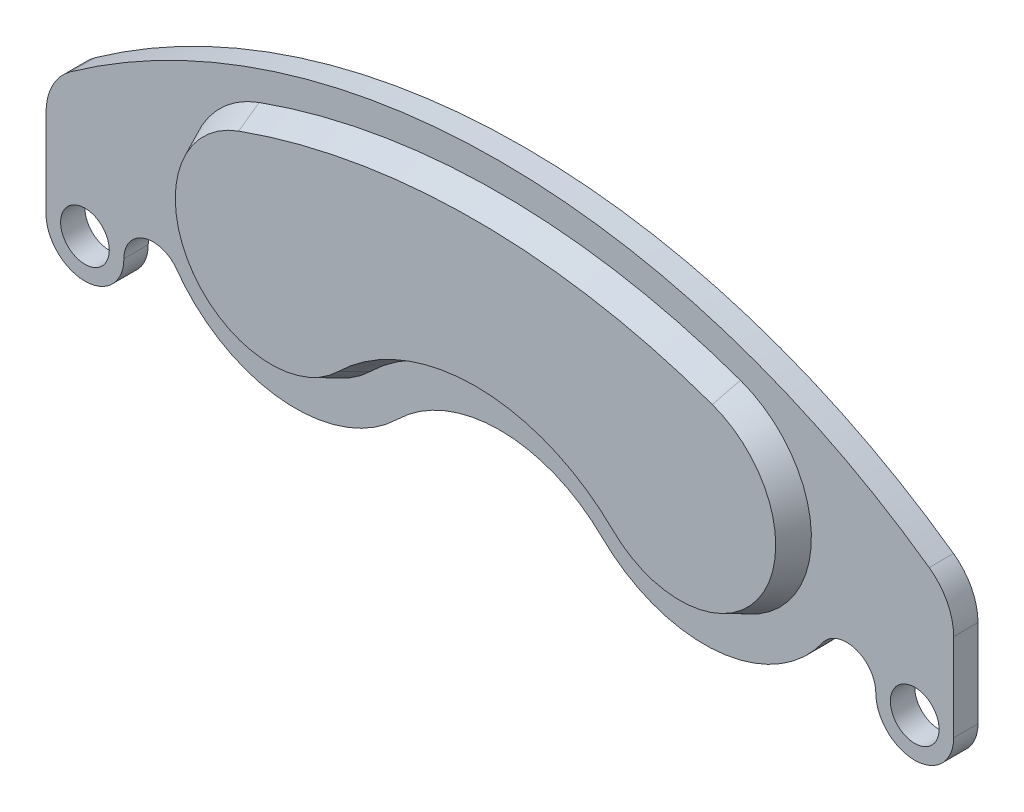
SolidWorks part; units mm, degrees
ref_plane "Front Plane" through (0, 0, 0) normal (0, 0, 1) x (1, 0, 0)
ref_plane "Top Plane" through (0, 0, 0) normal (0, 1, 0) x (1, 0, 0)
ref_plane "Right Plane" through (0, 0, 0) normal (1, 0, 0) x (0, 0, -1)
sketch "Sketch1" plane through (0, 0, 0) normal (0, 0, 1) x (1, 0, 0)
  line L0 (0, 0) -> (0, 108.8478) construction
  line L1 (-46.618, 57.0103) -> (-46.618, 48.0103)
  line L2 (46.618, 57.0103) -> (46.618, 48.0103)
  arc A0 (44.0995, 61.8969) -> (-44.0995, 61.8969) centre (0, 0) ccw
  arc A1 (-44.0995, 61.8969) -> (-46.618, 57.0103) centre (-40.618, 57.0103) ccw
  arc A2 (-46.618, 48.0103) -> (-38.618, 48.0103) centre (-42.618, 48.0103) ccw
  arc A3 (-38.618, 48.0103) -> (-33.3012, 49.9163) centre (-35.618, 48.0103) cw
  arc A4 (-33.3012, 49.9163) -> (-10.5, 47.7879) centre (-21, 58.5) ccw
  arc A5 (-10.5, 47.7879) -> (10.5, 47.7879) centre (0, 37.0757) cw
  arc A7 (33.3012, 49.9163) -> (10.5, 47.7879) centre (21, 58.5) cw
  arc A8 (38.618, 48.0103) -> (33.3012, 49.9163) centre (35.618, 48.0103) ccw
  arc A9 (46.618, 48.0103) -> (38.618, 48.0103) centre (42.618, 48.0103) cw
  arc A10 (44.0995, 61.8969) -> (46.618, 57.0103) centre (40.618, 57.0103) cw
  dimension "D1" = 76
  dimension "D2" = 6
  dimension "D4" = 4
  dimension "D5" = 3
  dimension "D6" = 15
  dimension "D3" = 9
  dimension "D7" = 58.5
  dimension "D8" = 42
extrude "Boss-Extrude1" add sketch "Sketch1" along normal mid plane 2.5
sketch "Sketch2" plane through (0, 0, 1.25) normal (0, 0, 1) x (1, 0, 0)
  line L0 (0, 0) -> (2.2126, 100.4432) construction
  arc A0 (24.7182, 68.8578) -> (-24.7182, 68.8578) centre (0, 0) ccw
  arc A1 (-24.7182, 68.8578) -> (-13.2965, 50.6409) centre (-21, 58.5) ccw
  arc A2 (-13.2965, 50.6409) -> (13.2965, 50.6409) centre (0, 37.0757) cw
  arc A3 (13.2965, 50.6409) -> (24.7182, 68.8578) centre (21, 58.5) ccw
  arc A5 (44.0995, 61.8969) -> (-44.0995, 61.8969) centre (0, 0) ccw construction
  arc A6 (-33.3012, 49.9163) -> (-10.5, 47.7879) centre (-21, 58.5) ccw construction
  arc A7 (10.5, 47.7879) -> (-10.5, 47.7879) centre (0, 37.0757) ccw construction
  arc A8 (10.5, 47.7879) -> (33.3012, 49.9163) centre (21, 58.5) ccw construction
  dimension "D1" = 73.16
extrude "Boss-Extrude2" add sketch "Sketch2" along normal blind 2.5 draft 25
sketch "Sketch3" plane through (0, 0, 1.25) normal (0, 0, 1) x (1, 0, 0)
  circle A1 centre (-42.618, 48.0103) radius 2.5
  circle A2 centre (42.618, 48.0103) radius 2.5
  dimension "D1" = 5
  dimension "D2" = 5
extrude "Cut-Extrude1" cut sketch "Sketch3" against normal through all
